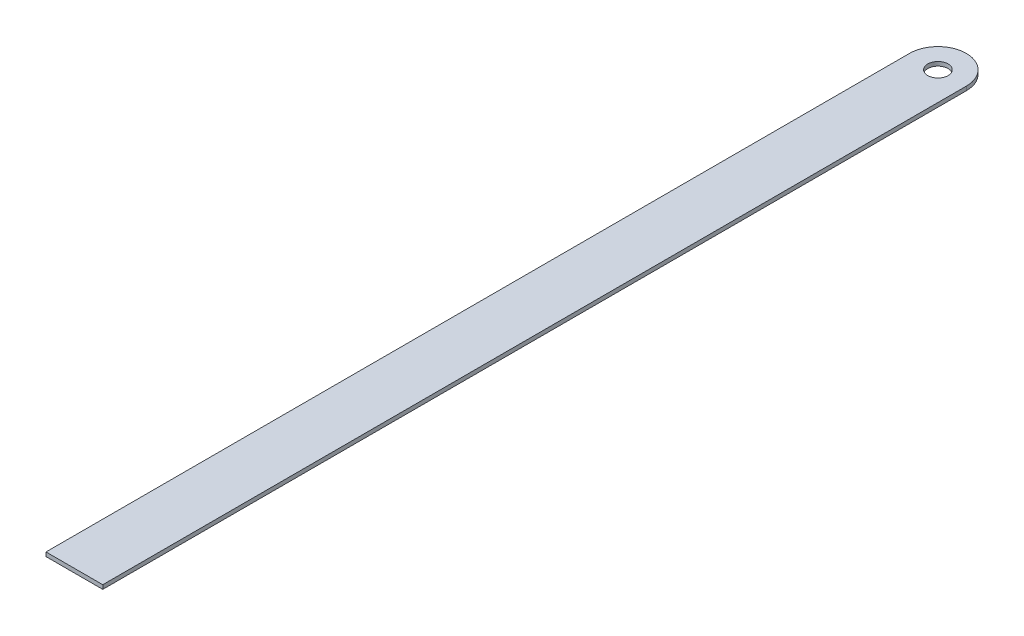
SolidWorks part; units mm, degrees
ref_plane "Front Plane" through (0, 0, 0) normal (0, 0, 1) x (1, 0, 0)
ref_plane "Top Plane" through (0, 0, 0) normal (0, 1, 0) x (1, 0, 0)
ref_plane "Right Plane" through (0, 0, 0) normal (1, 0, 0) x (0, 0, -1)
sketch "Sketch1" plane through (0, 0, 0) normal (0, 1, 0) x (1, 0, 0)
  line L1 (0, 0) -> (14, 0)
  line L2 (0, 0) -> (0, 200)
  line L3 (0, 200) -> (14, 200)
  line L4 (14, 0) -> (14, 200)
  dimension "D1" = 14
  dimension "D2" = 200
extrude "Boss-Extrude1" add sketch "Sketch1" along normal blind 1
sketch "Sketch2" plane through (0, 0, 0) normal (0, -1, 0) x (1, 0, 0)
  line L0 (0, -200) -> (0, 0) construction
  line L5 (0, -200) -> (14, -200)
  line L6 (0, -200) -> (0, -213)
  line L8 (14, -200) -> (14, -213)
  circle A2 centre (7, -213) radius 2.5
  arc A3 (0, -213) -> (14, -213) centre (7, -213) ccw
  dimension "D1" = 5
  dimension "D2" = 7
  dimension "D3" = 213
extrude "Boss-Extrude2" add sketch "Sketch2" against normal up to surface (1 mm away) up to face at (7, 1, -100)
